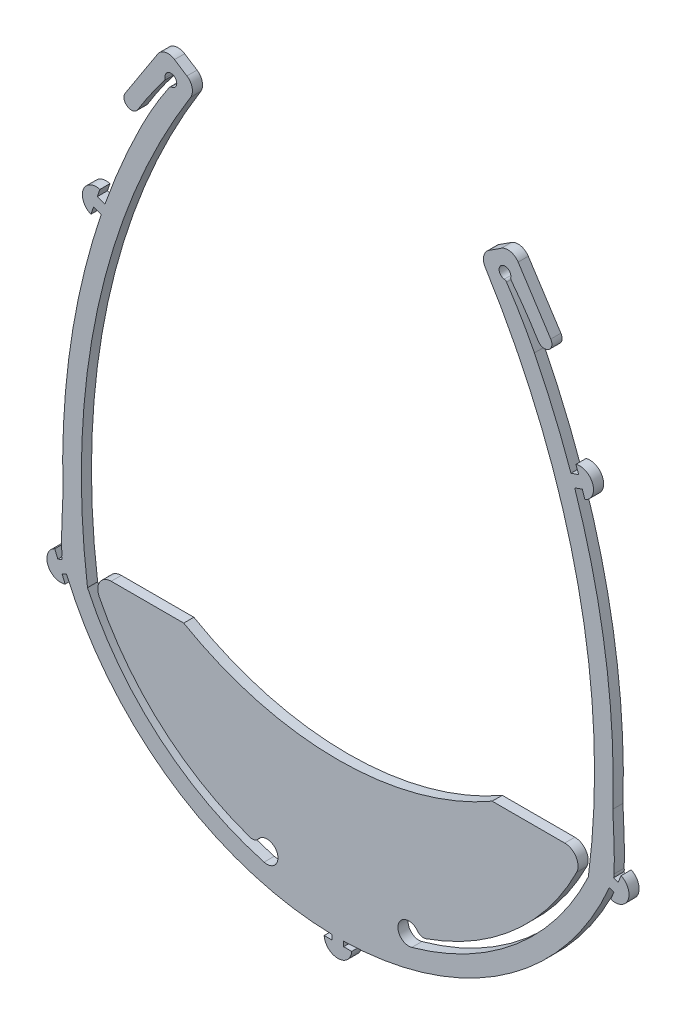
SolidWorks part; units mm, degrees
material "5052-H32"
ref_plane "Plan de face" through (0, 0, 0) normal (0, 0, 1) x (1, 0, 0)
ref_plane "Plan de dessus" through (0, 0, 0) normal (0, 1, 0) x (1, 0, 0)
ref_plane "Plan de droite" through (0, 0, 0) normal (1, 0, 0) x (0, 0, -1)
sketch "Sketch1" plane through (0, 0, 0) normal (0, 0, 1) x (1, 0, 0)
  line L0 (-38.2321, -48.335) -> (-60.9614, -48.335)
  line L1 (81.151, -48.335) -> (58.4218, -48.335)
  line L2 (61.2933, 103.1557) -> (57.4262, 100.6499)
  line L3 (76.7892, 86.255) -> (66.5681, 102.0289)
  line L4 (76.0435, 83.0431) -> (76.1127, 83.0879)
  line L5 (85.5131, 53.8296) -> (83.1209, 53.0059)
  line L6 (84.6885, 56.2244) -> (85.5131, 53.8296)
  line L7 (86.6734, 50.4598) -> (87.498, 48.065)
  line L8 (84.2812, 49.6361) -> (86.6734, 50.4598)
  line L9 (97.8748, -50.6982) -> (96.4544, -50.1243)
  line L10 (98.8236, -48.3498) -> (97.8748, -50.6982)
  line L11 (96.5397, -54.0026) -> (95.5909, -56.351)
  line L12 (95.1388, -53.4366) -> (96.5397, -54.0026)
  line L13 (11.8768, -111.1085) -> (11.8768, -109.5975)
  line L14 (14.4096, -111.1085) -> (11.8768, -111.1085)
  line L15 (8.3128, -111.1085) -> (5.7801, -111.1085)
  line L16 (8.3128, -109.5975) -> (8.3128, -111.1085)
  line L17 (-76.35, -54.0026) -> (-74.9491, -53.4366)
  line L18 (-75.4012, -56.351) -> (-76.35, -54.0026)
  line L19 (-77.6851, -50.6982) -> (-78.6339, -48.3498)
  line L20 (-76.2648, -50.1243) -> (-77.6851, -50.6982)
  line L21 (-66.4837, 50.4598) -> (-64.0916, 49.6361)
  line L22 (-67.3083, 48.065) -> (-66.4837, 50.4598)
  line L23 (-65.3234, 53.8296) -> (-64.4988, 56.2244)
  line L24 (-62.9313, 53.0059) -> (-65.3234, 53.8296)
  line L25 (-55.923, 83.0879) -> (-55.8539, 83.0431)
  line L26 (-46.3784, 102.0289) -> (-56.5996, 86.255)
  line L27 (-37.2366, 100.6499) -> (-41.1036, 103.1557)
  line L28 (76.1795, 82.8332) -> (76.2486, 82.8781)
  line L29 (76.999, 86.3909) -> (66.7779, 102.1649)
  line L30 (61.1573, 103.3655) -> (57.2903, 100.8597)
  line L31 (81.151, -48.085) -> (58.3548, -48.085)
  line L32 (-38.1652, -48.085) -> (-60.9614, -48.085)
  line L33 (-37.1006, 100.8597) -> (-40.9677, 103.3655)
  line L34 (-46.5882, 102.1649) -> (-56.8094, 86.3909)
  line L35 (-56.059, 82.8781) -> (-55.9898, 82.8332)
  line L36 (-63.0843, 53.323) -> (-65.0056, 53.9846)
  line L37 (-65.0056, 53.9846) -> (-64.1787, 56.3862)
  line L38 (-67.1557, 47.7404) -> (-66.3287, 50.142)
  line L39 (-66.3287, 50.142) -> (-64.4074, 49.4804)
  line L40 (-76.6049, -49.9921) -> (-77.547, -50.3727)
  line L41 (-77.547, -50.3727) -> (-78.4985, -48.0177)
  line L42 (-75.0731, -56.4958) -> (-76.0246, -54.1408)
  line L43 (-76.0246, -54.1408) -> (-75.0825, -53.7602)
  line L44 (8.0628, -109.8424) -> (8.0628, -110.8584)
  line L45 (8.0628, -110.8584) -> (5.5228, -110.8584)
  line L46 (14.6668, -110.8584) -> (12.1268, -110.8584)
  line L47 (12.1268, -110.8584) -> (12.1268, -109.8424)
  line L48 (95.2722, -53.7602) -> (96.2142, -54.1408)
  line L49 (96.2142, -54.1408) -> (95.2627, -56.4958)
  line L50 (98.6881, -48.0177) -> (97.7366, -50.3727)
  line L51 (97.7366, -50.3727) -> (96.7946, -49.9921)
  line L52 (84.5971, 49.4804) -> (86.5184, 50.142)
  line L53 (86.5184, 50.142) -> (87.3453, 47.7404)
  line L54 (84.3683, 56.3862) -> (85.1953, 53.9846)
  line L55 (85.1953, 53.9846) -> (83.274, 53.323)
  arc A0 (-36.0737, 95.432) -> (-68.38, -53.8016) centre (155.9937, -24.2607) ccw
  arc A1 (-68.38, -53.8016) -> (-13.0453, -100.6163) centre (10.0948, -17.1547) ccw
  arc A2 (-13.0453, -100.6163) -> (-14.8715, -95.2625) centre (-12.1302, -97.3158) ccw
  arc A3 (-17.4594, -96.0515) -> (-14.8715, -95.2625) centre (-16.7043, -93.8896) ccw
  arc A4 (-64.7167, -54.3996) -> (-17.4594, -96.0515) centre (10.0948, -17.1547) ccw
  arc A5 (-60.9614, -48.335) -> (-64.7167, -54.3996) centre (-60.9614, -52.53) ccw
  arc A6 (-38.2321, -48.335) -> (58.4218, -48.335) centre (10.0948, 35.5038) ccw
  arc A7 (84.9063, -54.3996) -> (81.151, -48.335) centre (81.151, -52.53) ccw
  arc A8 (37.649, -96.0515) -> (84.9063, -54.3996) centre (10.0948, -17.1547) ccw
  arc A9 (35.0611, -95.2625) -> (37.649, -96.0515) centre (36.894, -93.8896) ccw
  arc A10 (35.0611, -95.2625) -> (33.2349, -100.6163) centre (32.3198, -97.3158) ccw
  arc A11 (33.2349, -100.6163) -> (88.5697, -53.8016) centre (10.0948, -17.1547) ccw
  arc A12 (88.5697, -53.8016) -> (56.2634, 95.432) centre (-135.804, -24.2607) ccw
  arc A13 (57.4262, 100.6499) -> (56.2634, 95.432) centre (59.5003, 97.4492) ccw
  arc A14 (66.5681, 102.0289) -> (61.2933, 103.1557) centre (63.3673, 99.9549) ccw
  arc A15 (76.1127, 83.0879) -> (76.7892, 86.255) centre (74.8674, 85.0097) ccw
  arc A16 (72.8473, 83.7658) -> (76.0435, 83.0431) centre (74.7982, 84.9649) ccw
  arc A17 (72.8473, 83.7658) -> (64.4438, 95.9199) centre (-44.0959, 11.8926) ccw
  arc A18 (64.2461, 96.7228) -> (64.4438, 95.9199) centre (65.2504, 96.5443) ccw
  arc A19 (64.2461, 96.7228) -> (62.2106, 95.2208) centre (62.437, 97.0444) ccw
  arc A20 (62.928, 94.7828) -> (62.2106, 95.2208) centre (62.0849, 94.2086) ccw
  arc A21 (71.6595, 79.937) -> (62.928, 94.7828) centre (-44.6463, 21.5229) ccw
  arc A22 (83.1209, 53.0059) -> (71.6595, 79.937) centre (-135.804, -24.2607) ccw
  arc A23 (87.498, 48.065) -> (84.6885, 56.2244) centre (85.8568, 52.0633) ccw
  arc A24 (96.24, -31.5962) -> (84.2812, 49.6361) centre (-135.804, -24.2607) ccw
  arc A25 (96.4544, -50.1243) -> (96.6033, -49.0359) centre (95.2419, -49.404) ccw
  arc A26 (95.5909, -56.351) -> (98.8236, -48.3498) centre (96.9754, -52.2567) ccw
  arc A27 (11.8768, -109.5975) -> (95.1388, -53.4366) centre (10.0948, -17.1547) ccw
  arc A28 (5.7801, -111.1085) -> (14.4096, -111.1085) centre (10.0948, -110.8584) ccw
  arc A29 (-74.9491, -53.4366) -> (8.3128, -109.5975) centre (10.0948, -17.1547) ccw
  arc A30 (-78.6339, -48.3498) -> (-75.4012, -56.351) centre (-76.7858, -52.2567) ccw
  arc A31 (-76.4137, -49.0359) -> (-76.2648, -50.1243) centre (-75.0522, -49.404) ccw
  arc A32 (-64.0916, 49.6361) -> (-76.0504, -31.5962) centre (155.9937, -24.2607) ccw
  arc A33 (-64.4988, 56.2244) -> (-67.3083, 48.065) centre (-65.6672, 52.0633) ccw
  arc A34 (-51.4698, 79.937) -> (-62.9313, 53.0059) centre (155.9937, -24.2607) ccw
  arc A35 (-42.7384, 94.7828) -> (-51.4698, 79.937) centre (64.8359, 21.5229) ccw
  arc A36 (-42.0209, 95.2208) -> (-42.7384, 94.7828) centre (-41.8953, 94.2086) ccw
  arc A37 (-42.0209, 95.2208) -> (-44.0565, 96.7228) centre (-42.2473, 97.0444) ccw
  arc A38 (-44.2542, 95.9199) -> (-44.0565, 96.7228) centre (-45.0607, 96.5443) ccw
  arc A39 (-44.2542, 95.9199) -> (-52.6576, 83.7658) centre (64.2855, 11.8926) ccw
  arc A40 (-55.8539, 83.0431) -> (-52.6576, 83.7658) centre (-54.6086, 84.9649) ccw
  arc A41 (-56.5996, 86.255) -> (-55.923, 83.0879) centre (-54.6778, 85.0097) ccw
  arc A42 (-41.1036, 103.1557) -> (-46.3784, 102.0289) centre (-43.1776, 99.9549) ccw
  arc A43 (-36.0737, 95.432) -> (-37.2366, 100.6499) centre (-39.3106, 97.4492) ccw
  arc A44 (64, 96.7665) -> (62.2414, 95.469) centre (62.437, 97.0444) ccw
  arc A45 (64, 96.7665) -> (64.2461, 95.7668) centre (65.2504, 96.5443) ccw
  arc A46 (72.6343, 83.6349) -> (64.2461, 95.7668) centre (-44.0959, 11.8926) ccw
  arc A47 (72.6343, 83.6349) -> (76.1795, 82.8332) centre (74.7982, 84.9649) ccw
  arc A48 (76.2486, 82.8781) -> (76.999, 86.3909) centre (74.8674, 85.0097) ccw
  arc A49 (66.7779, 102.1649) -> (61.1573, 103.3655) centre (63.3673, 99.9549) ccw
  arc A50 (57.2903, 100.8597) -> (56.0512, 95.2998) centre (59.5003, 97.4492) ccw
  arc A51 (88.3268, -53.7307) -> (56.0512, 95.2998) centre (-135.804, -24.2607) ccw
  arc A52 (33.1681, -100.3753) -> (88.3268, -53.7307) centre (10.0948, -17.1547) ccw
  arc A53 (34.861, -95.4123) -> (33.1681, -100.3753) centre (32.3198, -97.3158) ccw
  arc A54 (34.861, -95.4123) -> (37.7314, -96.2876) centre (36.894, -93.8896) ccw
  arc A55 (37.7314, -96.2876) -> (85.1302, -54.511) centre (10.0948, -17.1547) ccw
  arc A56 (85.1302, -54.511) -> (81.151, -48.085) centre (81.151, -52.53) ccw
  arc A57 (-38.1652, -48.085) -> (58.3548, -48.085) centre (10.0948, 35.5038) ccw
  arc A58 (-60.9614, -48.085) -> (-64.9405, -54.511) centre (-60.9614, -52.53) ccw
  arc A59 (-64.9405, -54.511) -> (-17.5418, -96.2876) centre (10.0948, -17.1547) ccw
  arc A60 (-17.5418, -96.2876) -> (-14.6714, -95.4123) centre (-16.7043, -93.8896) ccw
  arc A61 (-12.9785, -100.3753) -> (-14.6714, -95.4123) centre (-12.1302, -97.3158) ccw
  arc A62 (-68.1372, -53.7307) -> (-12.9785, -100.3753) centre (10.0948, -17.1547) ccw
  arc A63 (-35.8615, 95.2998) -> (-68.1372, -53.7307) centre (155.9937, -24.2607) ccw
  arc A64 (-35.8615, 95.2998) -> (-37.1006, 100.8597) centre (-39.3106, 97.4492) ccw
  arc A65 (-40.9677, 103.3655) -> (-46.5882, 102.1649) centre (-43.1776, 99.9549) ccw
  arc A66 (-56.8094, 86.3909) -> (-56.059, 82.8781) centre (-54.6778, 85.0097) ccw
  arc A67 (-55.9898, 82.8332) -> (-52.4446, 83.6349) centre (-54.6086, 84.9649) ccw
  arc A68 (-44.0565, 95.7668) -> (-52.4446, 83.6349) centre (64.2855, 11.8926) ccw
  arc A69 (-44.0565, 95.7668) -> (-43.8103, 96.7665) centre (-45.0607, 96.5443) ccw
  arc A70 (-42.0517, 95.469) -> (-43.8103, 96.7665) centre (-42.2473, 97.0444) ccw
  arc A71 (-42.0517, 95.469) -> (-42.945, 94.9235) centre (-41.8953, 94.2086) ccw
  arc A72 (-42.945, 94.9235) -> (-51.6933, 80.0492) centre (64.8359, 21.5229) ccw
  arc A73 (-51.6933, 80.0492) -> (-63.0843, 53.323) centre (155.9937, -24.2607) ccw
  arc A74 (-64.1787, 56.3862) -> (-67.1557, 47.7404) centre (-65.6672, 52.0633) ccw
  arc A75 (-64.4074, 49.4804) -> (-76.3005, -31.5968) centre (155.9937, -24.2607) ccw
  arc A76 (-76.6654, -49.0109) -> (-76.6049, -49.9921) centre (-75.0522, -49.404) ccw
  arc A77 (-78.4985, -48.0177) -> (-75.0731, -56.4958) centre (-76.7858, -52.2567) ccw
  arc A78 (-75.0825, -53.7602) -> (8.0628, -109.8424) centre (10.0948, -17.1547) ccw
  arc A79 (5.5228, -110.8584) -> (14.6668, -110.8584) centre (10.0948, -110.8584) ccw
  arc A80 (12.1268, -109.8424) -> (95.2722, -53.7602) centre (10.0948, -17.1547) ccw
  arc A81 (95.2627, -56.4958) -> (98.6881, -48.0177) centre (96.9754, -52.2567) ccw
  arc A82 (96.7946, -49.9921) -> (96.855, -49.0109) centre (95.2419, -49.404) ccw
  arc A83 (96.4902, -31.5968) -> (84.5971, 49.4804) centre (-135.804, -24.2607) ccw
  arc A84 (87.3453, 47.7404) -> (84.3683, 56.3862) centre (85.8568, 52.0633) ccw
  arc A85 (83.274, 53.323) -> (71.8829, 80.0492) centre (-135.804, -24.2607) ccw
  arc A86 (71.8829, 80.0492) -> (63.1346, 94.9235) centre (-44.6463, 21.5229) ccw
  arc A87 (63.1346, 94.9235) -> (62.2414, 95.469) centre (62.0849, 94.2086) ccw
  spline S0 degree 3 poles (-76.3005, -31.5968) (-76.4574, -37.4427) (-76.9741, -43.2218) (-76.6654, -49.0109) knots 0.053468 0.053468 0.053468 0.053468 1 1 1 1
  spline S1 degree 3 poles (96.855, -49.0109) (97.1638, -43.2218) (96.6471, -37.4427) (96.4902, -31.5968) knots 0.053468 0.053468 0.053468 0.053468 1 1 1 1
  spline S2 degree 3 poles (96.24, -31.5962) (96.2793, -33.0598) (96.4034, -35.9914) (96.6126, -40.3526) (96.7342, -44.6992) (96.6804, -47.5916) (96.6033, -49.0359) knots 0.051382 0.051382 0.051382 0.051382 0.288635 0.525888 0.763141 1.000394 1.000394 1.000394 1.000394
  spline S3 degree 3 poles (-76.4137, -49.0359) (-76.4907, -47.5916) (-76.5445, -44.6992) (-76.4229, -40.3526) (-76.2137, -35.9914) (-76.0897, -33.0598) (-76.0504, -31.5962) knots 0.053074 0.053074 0.053074 0.053074 0.290327 0.52758 0.764833 1.002086 1.002086 1.002086 1.002086
extrude "Boss-Extrude1" add sketch "Sketch1" along normal blind 3.175 contours A43 L27 A42 L26 A41 L25 A40 A39 A38 A37 A36 A35 A34 L24 L23 A33 L22 L21 A32 S3 A31 L20 L19 A30 L18 L17 A29 L16 L15 A28 L14 L13 A27 L12 L11 A26 L10 L9 A25 S2 A24 L8 L7 A23 L6 L5 A22 A21 A20 A19 A18 A17 A16 L4 A15 L3 A14 L2 A13 A12 A11 A10 A9 A8 A7 L1 A6 L0 A5 A4 A3 A2 A1 A0
